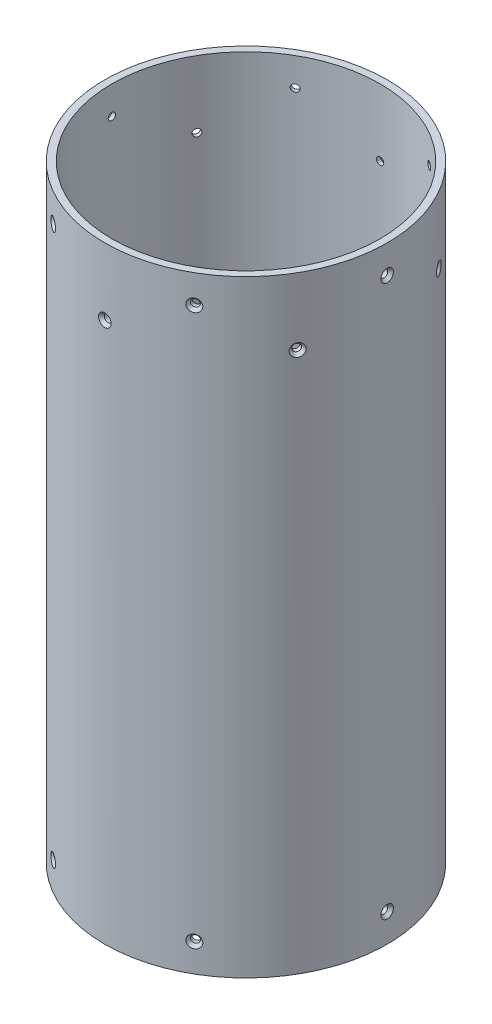
SolidWorks part; units mm, degrees
ref_plane "Front Plane" through (0, 0, 0) normal (0, 0, 1) x (1, 0, 0)
ref_plane "Top Plane" through (0, 0, 0) normal (0, 1, 0) x (1, 0, 0)
ref_plane "Right Plane" through (0, 0, 0) normal (1, 0, 0) x (0, 0, -1)
sketch "Sketch2" plane through (0, 0, 0) normal (0, 1, 0) x (1, 0, 0)
  circle A0 centre (0, 0) radius 63.5
extrude "Boss-Extrude1" add sketch "Sketch2" along normal blind 273.05
sketch "Sketch3" plane through (0, 273.05, 0) normal (0, 1, 0) x (1, 0, 0)
  circle A0 centre (0, 0) radius 60.325
extrude "Cut-Extrude1" cut sketch "Sketch3" against normal blind 442
sketch "Sketch6" plane through (0, 0, 0) normal (0, 0, 1) x (1, 0, 0)
  circle A0 centre (0, 413.65) radius 1.5875
hole_wizard "#4" positions "3DSketch1" profile "Sketch7" countersink size "#4" standard "ANSI Inch"
sketch3d "3DSketch1"
  point P0 (0, 242.9574, -63.5)
sketch "Sketch7" plane through (0, 242.9574, -63.5) normal (1, 0, 0) x (0, 1, 0)
  line L0 (0, 0) -> (0, 145.9068)
  line L1 (0, 145.9068) -> (1.6319, 145.9068)
  line L2 (1.6319, 145.9068) -> (1.6319, 1.4098)
  line L3 (1.6319, 1.4098) -> (2.8575, 0)
  line L5 (2.8575, 0) -> (0, 0)
  line L6 (-1.6319, 1.4098) -> (-2.8575, 0) construction
  line L11 (0, -6.35) -> (0, 107.95) construction
  dimension "Thru Hole Dia." = 3.2639
  dimension "Thru Hole Depth" = 145.9068
  dimension "Near C'Sink Dia." = 5.715
  dimension "Near C'Sink Angle" = 82
pattern_circular "CirPattern1" count 6 every 60 about axis through (0, 273.05, 0) along (0, -1, 0) of "#4"
hole_wizard "CSK for #4 Flat Head Machine Screw1" positions "3DSketch2" profile "Sketch8" countersink size "#4" standard "ANSI Inch"
sketch3d "3DSketch2"
  point P0 (63.5, 260.35, 0)
sketch "Sketch8" plane through (63.5, 260.35, 0) normal (0, 1, 0) x (0, 0, -1)
  line L0 (0, 0) -> (0, 145.9068)
  line L1 (0, 145.9068) -> (1.6319, 145.9068)
  line L2 (1.6319, 145.9068) -> (1.6319, 1.4098)
  line L3 (1.6319, 1.4098) -> (2.8575, 0)
  line L5 (2.8575, 0) -> (0, 0)
  line L6 (-1.6319, 1.4098) -> (-2.8575, 0) construction
  line L11 (0, -6.35) -> (0, 107.95) construction
  dimension "Thru Hole Dia." = 3.2639
  dimension "Thru Hole Depth" = 145.9068
  dimension "Near C'Sink Dia." = 5.715
  dimension "Near C'Sink Angle" = 82
pattern_circular "CirPattern2" count 6 every 60 about axis through (0, 273.05, 0) along (0, -1, 0) of "CSK for #4 Flat Head Machine Screw1"
ref_plane "Plane1" through (0, 136.525, 0) normal (0, 1, 0) x (1, 0, 0)
mirror "Mirror1" about plane through (0, 136.525, 0) normal (0, 1, 0) of "CirPattern2", "CSK for #4 Flat Head Machine Screw1"
